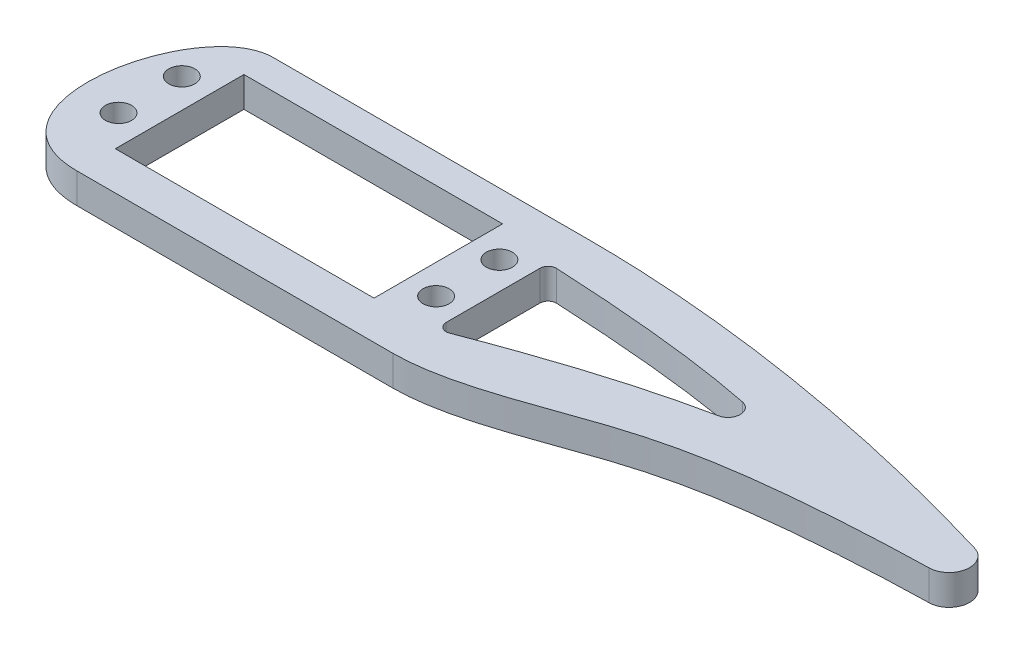
SolidWorks part; units mm, degrees
material "Custom Plastic"
ref_plane "Front Plane" through (0, 0, 0) normal (0, 0, 1) x (1, 0, 0)
ref_plane "Top Plane" through (0, 0, 0) normal (0, 1, 0) x (1, 0, 0)
ref_plane "Right Plane" through (0, 0, 0) normal (1, 0, 0) x (0, 0, -1)
sketch "Sketch1" plane through (0, 0, 0) normal (0, 1, 0) x (1, 0, 0)
  line L0 (0, 0) -> (102.8065, 0) construction
  line L1 (0, 0) -> (-31.0515, 0) construction
  line L2 (-20.1295, 14.5796) -> (29.0195, 14.5796)
  line L3 (-20.1295, -10.0076) -> (20.1295, -10.0076) construction
  line L4 (-20.1295, -10.0076) -> (-20.1295, 10.0076) construction
  line L5 (-20.1295, 10.0076) -> (20.1295, 10.0076) construction
  line L6 (20.1295, -10.0076) -> (20.1295, 10.0076) construction
  line L7 (-20.1295, -10.0076) -> (20.1295, 10.0076) construction
  line L8 (-20.1295, 10.0076) -> (20.1295, -10.0076) construction
  line L9 (-20.1295, -15.9766) -> (29.0195, -15.9766)
  line L10 (29.0195, 14.5796) -> (29.0195, -15.9766) construction
  circle A0 centre (99.6315, 0) radius 3.175 construction
  arc A1 (99.6999, -3.1743) -> (100.5403, 3.0422) centre (99.6315, 0) ccw
  spline S0 degree 3 poles (-20.1295, 14.5796) (-25.6505, 14.5796) (-34.7055, -0.2252) (-29.3835, -15.9766) (-20.1295, -15.9766) knots 0 0 0 0 0.484879 1 1 1 1
  spline S1 degree 3 poles (29.0195, 14.5796) (61.6763, 14.5796) (92.6265, 5.4062) (100.5403, 3.0422) knots 0 0 0 0 1 1 1 1
  spline S2 degree 3 poles (29.0195, -15.9766) (36.7524, -15.9766) (47.4488, -11.6621) (61.5632, -6.9643) (74.7544, -4.3444) (91.2459, -3.3565) (99.6999, -3.1743) knots 0 0 0 0 0.316403 0.381997 0.655941 1 1 1 1
  dimension "D7" = 6.35
  dimension "D1" = 133.858
  dimension "D2" = 20.0152
  dimension "D3" = 40.259
  dimension "D4" = 5.969
  dimension "D5" = 4.572
  dimension "D6" = 10.922
  dimension "D8" = 8.89
extrude "Boss-Extrude1" add sketch "Sketch1" along normal blind 4.699
sketch "Sketch2" plane through (0, 4.699, 0) normal (0, 1, 0) x (1, 0, 0)
  line L0 (29.0195, 0) -> (29.0195, 8.2621)
  line L1 (-20.1295, -10.0076) -> (20.1295, -10.0076)
  line L2 (-20.1295, -10.0076) -> (-20.1295, 10.0076)
  line L3 (-20.1295, 10.0076) -> (20.1295, 10.0076)
  line L4 (20.1295, -10.0076) -> (20.1295, 10.0076)
  line L5 (0, 0) -> (102.8065, 0) construction
  line L6 (29.0195, 14.5796) -> (29.0195, -15.9766) construction
  line L7 (29.0195, 0) -> (29.0195, -9.5179)
  line L8 (62.4205, 2.8031) -> (29.0195, 2.8031) construction
  line L9 (0, 0) -> (-24.7117, 0) construction
  line L10 (-24.7117, 0) -> (-24.7117, 4.9251) construction
  line L11 (-24.7117, 0) -> (-24.7117, -4.9251) construction
  line L12 (0, 0) -> (24.7117, 0) construction
  line L13 (24.7117, 0) -> (24.7117, 4.9251) construction
  line L14 (24.7117, 0) -> (24.7117, -4.9251) construction
  circle A1 centre (62.4205, 2.8031) radius 1.905 construction
  circle A3 centre (62.4205, 2.8031) radius 1.905
  arc A4 (62.7998, 0.9363) -> (62.8032, 4.6693) centre (62.4205, 2.8031) ccw
  circle A5 centre (-24.7117, 4.9251) radius 2.032
  circle A6 centre (-24.7117, -4.9251) radius 2.032
  circle A7 centre (24.7117, -4.9251) radius 2.032
  circle A8 centre (24.7117, 4.9251) radius 2.032
  spline S0 degree 2 poles (29.0195, 8.2621) (49.8218, 7.3313) (62.8032, 4.6693) knots 0 0 0 1 1 1
  spline S1 degree 2 poles (62.7998, 0.9363) (48.0685, -2.0566) (29.0195, -9.5179) knots 0 0 0 1 1 1
  dimension "D3" = 3.81
  dimension "D4" = 9.8501
  dimension "D6" = 4.064
  dimension "D1" = 17.78
  dimension "D2" = 33.401
  dimension "D5" = 49.4233
extrude "Cut-Extrude1" cut sketch "Sketch2" against normal through all contours L1 L4 L3 L2 | S1 A3 S0 L0 L7 | S1 A3 | A5 | A6 | A7 | A8
fillet "Fillet1" radius 1.27 2 edges at (29.0195, 2.3495, 9.5179) (29.0195, 2.3495, -8.2621)
